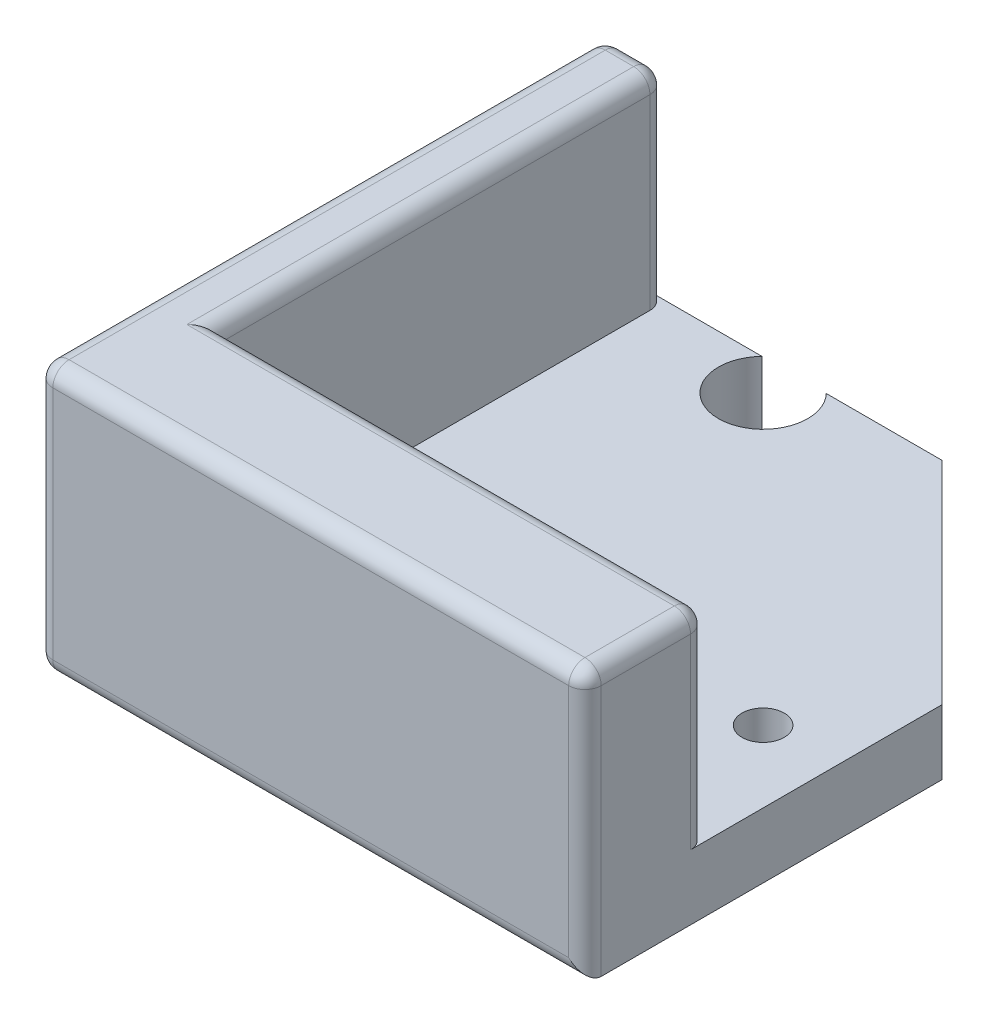
SolidWorks part; units mm, degrees
ref_plane "Front Plane" through (0, 0, 0) normal (0, 0, 1) x (1, 0, 0)
ref_plane "Top Plane" through (0, 0, 0) normal (0, 1, 0) x (1, 0, 0)
ref_plane "Right Plane" through (0, 0, 0) normal (1, 0, 0) x (0, 0, -1)
sketch "Sketch1" plane through (0, 0, 0) normal (0, 1, 0) x (1, 0, 0)
  line L0 (0, 0) -> (38.1, 0)
  line L1 (38.1, 0) -> (38.1, 2.3813)
  line L2 (38.1, 2.3813) -> (2.3813, 2.3812)
  line L3 (2.3813, 2.3812) -> (2.3812, 38.1)
  line L4 (2.3812, 38.1) -> (0, 38.1)
  line L5 (0, 38.1) -> (0, 0)
  dimension "D1" = 38.1
  dimension "D2" = 38.1
  dimension "D3" = 2.3813
  dimension "D4" = 2.3813
extrude "Boss-Extrude1" add sketch "Sketch1" along normal blind 2.54
sketch "Sketch2" plane through (0, 2.54, 0) normal (0, 1, 0) x (1, 0, 0)
  line L0 (2.3813, 2.3812) -> (2.3812, 38.1) construction
  line L1 (0, 38.1) -> (-9.525, 38.1)
  line L2 (0, 38.1) -> (0, 0)
  line L3 (0, 0) -> (-9.525, 0)
  line L4 (-9.525, 38.1) -> (-9.525, 0)
  line L5 (38.1, 0) -> (-9.525, 0)
  line L6 (38.1, 0) -> (38.1, -9.525)
  line L7 (38.1, -9.525) -> (-9.525, -9.525)
  line L8 (-9.525, 0) -> (-9.525, -9.525)
  line L9 (38.1, 2.3813) -> (2.3813, 2.3812) construction
  line M11 (0, 38.1) -> (0, 0)
  line M12 (0, 0) -> (38.1, 0)
  dimension "D1" = 11.9062
  dimension "D2" = 11.9062
extrude "Boss-Extrude2" add sketch "Sketch2" against normal blind 15.875 contours L1 L4 L3 M11 | L3 L8 L7 L6 M12
sketch "Sketch3" plane through (0, -13.335, 0) normal (0, -1, 0) x (-1, 0, 0)
  line L0 (-38.1, 0) -> (-38.1, -9.525) construction
  line L1 (9.525, -9.525) -> (-38.1, -9.525)
  line L2 (9.525, -9.525) -> (9.525, 38.1)
  line L3 (9.525, 38.1) -> (-18.3731, 38.1)
  line L4 (-38.1, -9.525) -> (-38.1, 18.3731)
  line L5 (0, 38.1) -> (9.525, 38.1) construction
  line L7 (-38.1, 18.3731) -> (-18.3731, 38.1)
  dimension "D1" = 45
extrude "Boss-Extrude3" add sketch "Sketch3" along normal blind 5.08
hole_wizard "M3 Clearance Hole1" positions "Sketch5" profile "Sketch6" hole size "M3" standard "ANSI Metric"
sketch "Sketch5" plane through (0, -18.415, 0) normal (0, -1, 0) x (-1, 0, 0)
  point P0 (-10, 32.5)
  point P2 (-32.5, 10)
  dimension "D1" = 32.5
  dimension "D2" = 32.5
  dimension "D3" = 10
  dimension "D4" = 10
sketch "Sketch6" plane through (10, -18.415, -32.5) normal (1, 0, 0) x (0, 0, -1)
  line L0 (0, 0) -> (0, 13.6914)
  line L1 (0, 13.6914) -> (1.65, 12.7)
  line L2 (1.65, 12.7) -> (1.65, 0)
  line L5 (1.65, 0) -> (0, 0)
  line L10 (0, 13.6914) -> (-1.65, 12.7) construction
  line L11 (0, -6.35) -> (0, 107.95) construction
  dimension "Hole Dia." = 3.3
  dimension "Hole Depth" = 12.7
  dimension "Drill Angle" = 118
sketch "Sketch7" plane through (0, 2.54, 0) normal (0, 1, 0) x (1, 0, 0)
  line L0 (2.3812, 0) -> (38.1, 0)
  line L1 (2.3812, 38.1) -> (0, 38.1)
  line L2 (2.3812, 38.1) -> (2.3812, 0)
  line L3 (2.3812, 0) -> (0, 0)
  line L4 (0, 38.1) -> (0, 0)
  line L9 (38.1, 0) -> (38.1, 2.3813)
  line L10 (38.1, 2.3813) -> (2.3813, 2.3812)
  line M1 (2.3812, 38.1) -> (-9.525, 38.1)
  line M4 (38.1, -9.525) -> (38.1, 2.3813)
  line M5 (38.1, 2.3813) -> (2.3813, 2.3812)
  line M6 (2.3813, 2.3812) -> (2.3812, 38.1)
extrude "Cut-Extrude1" cut sketch "Sketch7" against normal blind 2.54 contours L2 L0 M5 M4 | L4 L3 L2 M1 M6
fillet "Fillet1" radius 1.27 13 edges at (38.1, 2.54, 4.7625) (-4.7625, 2.54, -38.1) (0, 2.54, -19.05) (19.05, 2.54, 0) (38.1, -7.9375, 9.525) (14.2875, -18.415, 9.525) (14.2875, 2.54, 9.525) (-9.525, -7.9375, 9.525) (-9.525, -18.415, -14.2875) (-9.525, -7.9375, -38.1) (-9.525, 2.54, -14.2875) (0, -5.3975, -38.1) (38.1, -5.3975, 0)
sketch "Sketch8" plane through (0, -13.335, 0) normal (0, 1, 0) x (1, 0, 0)
  circle A0 centre (10, 32.5) radius 3.4925
  dimension "D1" = 6.985
extrude "Cut-Extrude2" cut sketch "Sketch8" against normal blind 10.16
sketch "Sketch9" plane through (0, -13.335, 0) normal (0, 1, 0) x (1, 0, 0)
  line L0 (-1.27, 38.1) -> (18.3731, 38.1) construction
  line L1 (25.8884, 38.1) -> (-15.1936, 38.1)
  line L2 (25.8884, 38.1) -> (25.8884, 34.925)
  line L3 (25.8884, 34.925) -> (-15.1936, 34.925)
  line L4 (-15.1936, 38.1) -> (-15.1936, 34.925)
  line L5 (-8.255, 38.1) -> (-1.27, 38.1) construction
  line L6 (-15.1936, 34.925) -> (-4.7625, 34.925)
  line L7 (-15.1936, 34.925) -> (-15.1936, -12.7812)
  line L8 (-15.1936, -12.7812) -> (-4.7625, -12.7812)
  line L9 (-4.7625, 34.925) -> (-4.7625, -12.7812)
  point P11 (-4.7625, 38.1)
  circle M5 centre (10, 32.5) radius 3.4925
  line M7 (18.3731, 38.1) -> (-1.27, 38.1)
  arc M8 (-1.27, 38.1) -> (0, 36.83) centre (-1.27, 36.83) cw
  line M9 (0, 36.83) -> (0, 0)
  line M13 (38.1, 18.3731) -> (18.3731, 38.1)
  dimension "D1" = 3.175
extrude "Cut-Extrude3" cut sketch "Sketch9" against normal through all both and the other way through all contours L9 L3 L7 L8 | L3 L2 L1 M13 | L3 M13 M7 M8 M9 M5 | L1 L4 L3 M9 M8
fillet "Fillet3" radius 1.27 9 edges at (-4.7625, 2.168, 9.153) (-4.7625, -7.9375, 9.525) (-0.372, 2.168, -34.925) (-3.0162, 2.54, -34.925) (-4.7625, -18.415, -13.335) (0, -6.0325, -34.925) (-4.7625, -18.043, 9.153) (-4.7625, -7.9375, -34.925) (-4.7625, 2.54, -13.335)
